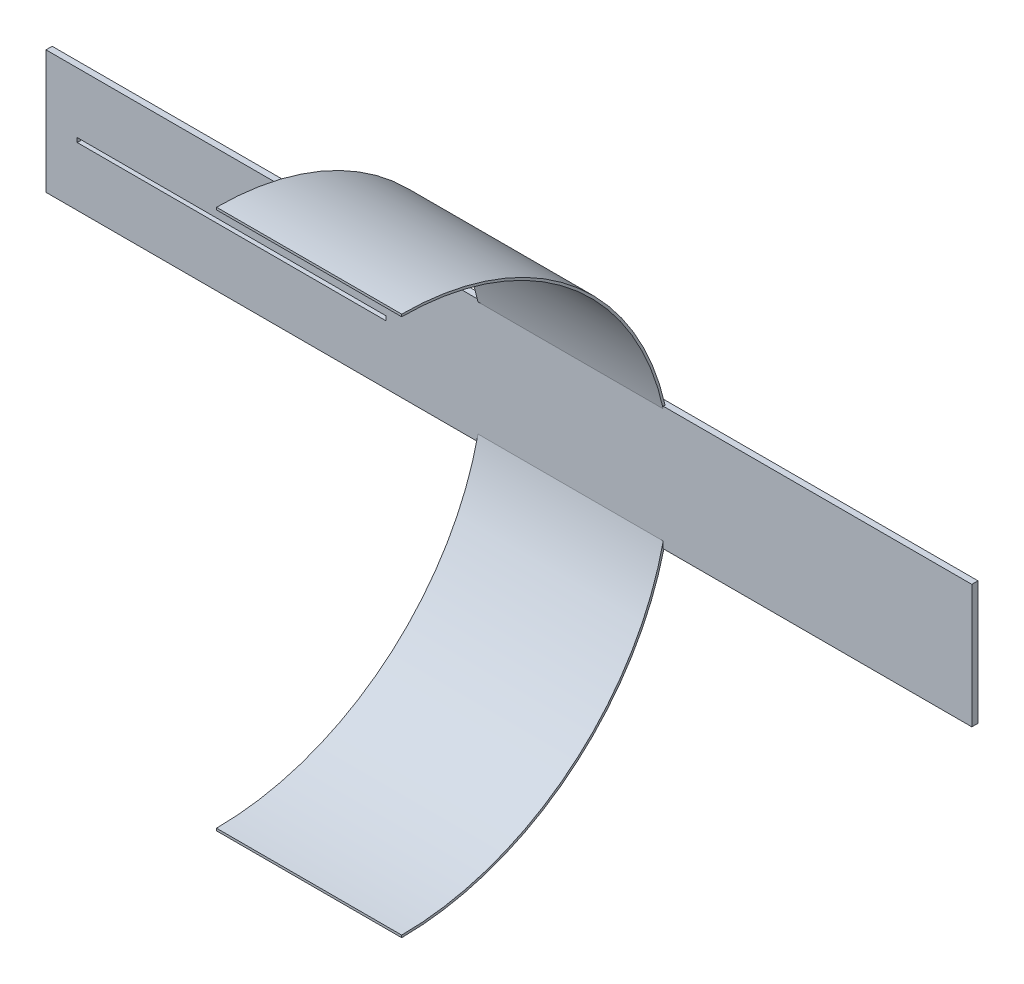
SolidWorks part; units mm, degrees
ref_plane "Front Plane" through (0, 0, 0) normal (0, 0, 1) x (1, 0, 0)
ref_plane "Top Plane" through (0, 0, 0) normal (0, 1, 0) x (1, 0, 0)
ref_plane "Right Plane" through (0, 0, 0) normal (1, 0, 0) x (0, 0, -1)
sketch "Szkic4" plane through (0, 0, 0) normal (0, 0, 1) x (1, 0, 0)
  line L0 (-0.0618, 10.1285) -> (-0.0618, -9.8715) construction
  line L1 (-30.0618, 10.1285) -> (119.9382, 10.1285)
  line L2 (-30.0618, 10.1285) -> (-30.0618, -9.8715)
  line L3 (-30.0618, -9.8715) -> (119.9382, -9.8715)
  line L4 (119.9382, 10.1285) -> (119.9382, -9.8715)
  line L6 (-25, -0.35) -> (25, -0.35)
  line L7 (-25, -0.35) -> (-25, 0.35)
  line L8 (-25, 0.35) -> (25, 0.35)
  line L9 (25, -0.35) -> (25, 0.35)
  line L10 (-25, -0.35) -> (25, 0.35) construction
  line L11 (-25, 0.35) -> (25, -0.35) construction
  point P6 (0, 0)
  dimension "D1" = 20
  dimension "D2" = 150
  dimension "D3" = 30
extrude "Dodanie-wyciągnięcie1" add sketch "Szkic4" along normal blind 1
sketch "Szkic6" plane through (0, 0, 1) normal (0, 0, 1) x (1, 0, 0)
  line L0 (119.9382, 0.1285) -> (69.9382, 0.1285) construction
  line L1 (119.9382, -9.8715) -> (119.9382, 10.1285) construction
ref_plane "Płaszczyzna1" through (69.9382, 0, 0) normal (1, 0, 0) x (0, 0, -1)
sketch "Szkic8" plane through (69.9382, 0, 0) normal (1, 0, 0) x (0, 0, -1)
  line L0 (-43.3742, 44.7493) -> (-43.3742, -43.7885)
  circle A0 centre (-43.3742, 0.4804) radius 43.75
  circle A1 centre (-43.3742, 0.4804) radius 43.3768
  point P7 (-43.3742, 0.4804)
extrude "Dodanie-wyciągnięcie2" add sketch "Szkic8" against normal blind 30 contours A1 L0 A0
